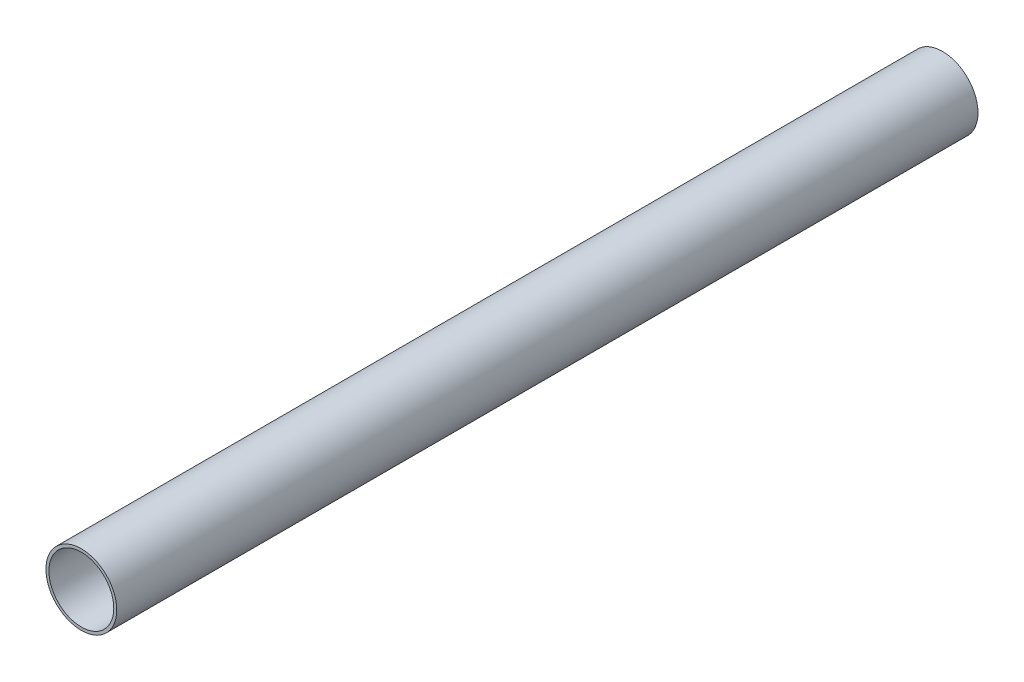
SolidWorks part; units mm, degrees
ref_plane "Front Plane" through (0, 0, 0) normal (0, 0, 1) x (1, 0, 0)
ref_plane "Top Plane" through (0, 0, 0) normal (0, 1, 0) x (1, 0, 0)
ref_plane "Right Plane" through (0, 0, 0) normal (1, 0, 0) x (0, 0, -1)
sketch "Motor Casing" plane through (0, 0, 0) normal (0, 0, 1) x (1, 0, 0)
  circle A1 centre (0, 0) radius 17.4625
  circle A4 centre (0, 0) radius 19.05 construction
  circle A5 centre (0, 0) radius 19.05
  dimension "D1" = 1.5875
extrude "Boss-Extrude1" add sketch "Motor Casing" along normal blind 463.55
